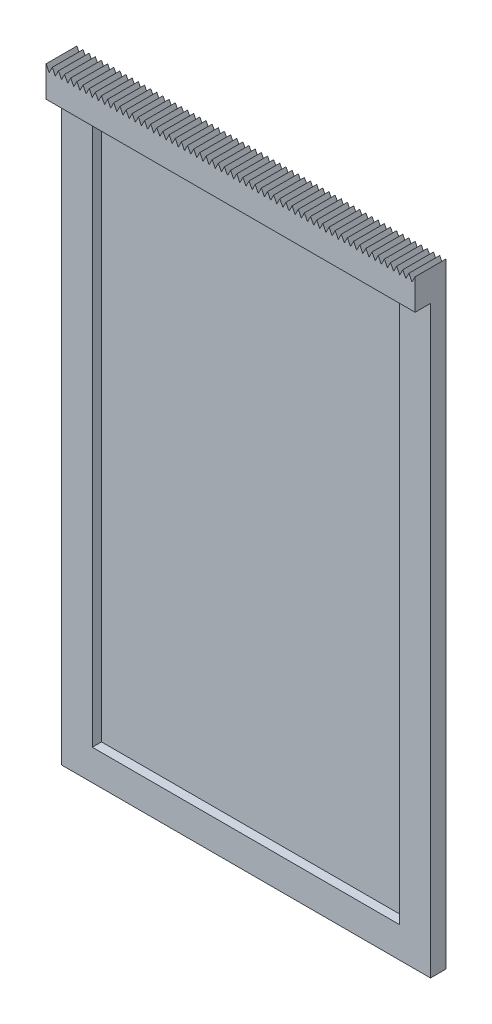
SolidWorks part; units mm, degrees
ref_plane "Alzado" through (0, 0, 0) normal (0, 0, 1) x (1, 0, 0)
ref_plane "Planta" through (0, 0, 0) normal (0, 1, 0) x (1, 0, 0)
ref_plane "Vista lateral" through (0, 0, 0) normal (1, 0, 0) x (0, 0, -1)
sketch "Croquis2" plane through (0, 0, 0) normal (0, 0, 1) x (1, 0, 0)
  line L0 (-60, 100) -> (60, -100) construction
  line L1 (-60, 100) -> (60, 100)
  line L2 (-60, 100) -> (-60, -100)
  line L3 (-60, -100) -> (60, -100)
  line L4 (60, 100) -> (60, -100)
  point P4 (0, 0)
  dimension "D1" = 120
  dimension "D2" = 200
extrude "Saliente-Extruir1" add sketch "Croquis2" along normal blind 5
sketch "Croquis3" plane through (0, 0, 5) normal (0, 0, 1) x (1, 0, 0)
  line L0 (-60, 100) -> (-60, -100) construction
  line L1 (-50, 90) -> (50, 90)
  line L2 (-50, 90) -> (-50, -90)
  line L3 (-50, -90) -> (50, -90)
  line L4 (50, 90) -> (50, -90)
  line L5 (-50, 90) -> (50, -90) construction
  line L6 (60, 100) -> (-60, 100) construction
  point P6 (0, 0)
  dimension "D1" = 10
  dimension "D2" = 10
extrude "Cortar-Extruir1" cut sketch "Croquis3" against normal blind 3
sketch "Croquis4" plane through (0, 0, 5) normal (0, 0, 1) x (1, 0, 0)
  line L0 (60, -100) -> (60, 100) construction
  line L1 (-60, 100) -> (60, 100)
  line L2 (-60, 100) -> (-60, 90)
  line L3 (-60, 90) -> (60, 90)
  line L4 (60, 100) -> (60, 90)
  dimension "D1" = 10
extrude "Saliente-Extruir3" add sketch "Croquis4" along normal blind 5
sketch "Croquis5" plane through (0, 100, 0) normal (0, 1, 0) x (1, 0, 0)
  line L0 (-60, -10) -> (-59, -8)
  line L1 (-59, -8) -> (-58, -10)
  line L2 (60, -10) -> (-60, -10) construction
  line L3 (-60, -10) -> (-58, -10)
  line L4 (-58, -10) -> (-56, -10)
  line L5 (-57, -8) -> (-56, -10)
  line L6 (-58, -10) -> (-57, -8)
  line L7 (-56, -10) -> (-54, -10)
  line L8 (-55, -8) -> (-54, -10)
  line L9 (-56, -10) -> (-55, -8)
  line L10 (-54, -10) -> (-52, -10)
  line L11 (-53, -8) -> (-52, -10)
  line L12 (-54, -10) -> (-53, -8)
  line L13 (-52, -10) -> (-50, -10)
  line L14 (-51, -8) -> (-50, -10)
  line L15 (-52, -10) -> (-51, -8)
  line L16 (-50, -10) -> (-48, -10)
  line L17 (-49, -8) -> (-48, -10)
  line L18 (-50, -10) -> (-49, -8)
  line L19 (-48, -10) -> (-46, -10)
  line L20 (-47, -8) -> (-46, -10)
  line L21 (-48, -10) -> (-47, -8)
  line L22 (-46, -10) -> (-44, -10)
  line L23 (-45, -8) -> (-44, -10)
  line L24 (-46, -10) -> (-45, -8)
  line L25 (-44, -10) -> (-42, -10)
  line L26 (-43, -8) -> (-42, -10)
  line L27 (-44, -10) -> (-43, -8)
  line L28 (-42, -10) -> (-40, -10)
  line L29 (-41, -8) -> (-40, -10)
  line L30 (-42, -10) -> (-41, -8)
  line L31 (-40, -10) -> (-38, -10)
  line L32 (-39, -8) -> (-38, -10)
  line L33 (-40, -10) -> (-39, -8)
  line L34 (-38, -10) -> (-36, -10)
  line L35 (-37, -8) -> (-36, -10)
  line L36 (-38, -10) -> (-37, -8)
  line L37 (-36, -10) -> (-34, -10)
  line L38 (-35, -8) -> (-34, -10)
  line L39 (-36, -10) -> (-35, -8)
  line L40 (-34, -10) -> (-32, -10)
  line L41 (-33, -8) -> (-32, -10)
  line L42 (-34, -10) -> (-33, -8)
  line L43 (-32, -10) -> (-30, -10)
  line L44 (-31, -8) -> (-30, -10)
  line L45 (-32, -10) -> (-31, -8)
  line L46 (-30, -10) -> (-28, -10)
  line L47 (-29, -8) -> (-28, -10)
  line L48 (-30, -10) -> (-29, -8)
  line L49 (-28, -10) -> (-26, -10)
  line L50 (-27, -8) -> (-26, -10)
  line L51 (-28, -10) -> (-27, -8)
  line L52 (-26, -10) -> (-24, -10)
  line L53 (-25, -8) -> (-24, -10)
  line L54 (-26, -10) -> (-25, -8)
  line L55 (-24, -10) -> (-22, -10)
  line L56 (-23, -8) -> (-22, -10)
  line L57 (-24, -10) -> (-23, -8)
  line L58 (-22, -10) -> (-20, -10)
  line L59 (-21, -8) -> (-20, -10)
  line L60 (-22, -10) -> (-21, -8)
  line L61 (-20, -10) -> (-18, -10)
  line L62 (-19, -8) -> (-18, -10)
  line L63 (-20, -10) -> (-19, -8)
  line L64 (-18, -10) -> (-16, -10)
  line L65 (-17, -8) -> (-16, -10)
  line L66 (-18, -10) -> (-17, -8)
  line L67 (-16, -10) -> (-14, -10)
  line L68 (-15, -8) -> (-14, -10)
  line L69 (-16, -10) -> (-15, -8)
  line L70 (-14, -10) -> (-12, -10)
  line L71 (-13, -8) -> (-12, -10)
  line L72 (-14, -10) -> (-13, -8)
  line L73 (-12, -10) -> (-10, -10)
  line L74 (-11, -8) -> (-10, -10)
  line L75 (-12, -10) -> (-11, -8)
  line L76 (-10, -10) -> (-8, -10)
  line L77 (-9, -8) -> (-8, -10)
  line L78 (-10, -10) -> (-9, -8)
  line L79 (-8, -10) -> (-6, -10)
  line L80 (-7, -8) -> (-6, -10)
  line L81 (-8, -10) -> (-7, -8)
  line L82 (-6, -10) -> (-4, -10)
  line L83 (-5, -8) -> (-4, -10)
  line L84 (-6, -10) -> (-5, -8)
  line L85 (-4, -10) -> (-2, -10)
  line L86 (-3, -8) -> (-2, -10)
  line L87 (-4, -10) -> (-3, -8)
  line L88 (-2, -10) -> (0, -10)
  line L89 (-1, -8) -> (0, -10)
  line L90 (-2, -10) -> (-1, -8)
  line L91 (0, -10) -> (2, -10)
  line L92 (1, -8) -> (2, -10)
  line L93 (0, -10) -> (1, -8)
  line L94 (2, -10) -> (4, -10)
  line L95 (3, -8) -> (4, -10)
  line L96 (2, -10) -> (3, -8)
  line L97 (4, -10) -> (6, -10)
  line L98 (5, -8) -> (6, -10)
  line L99 (4, -10) -> (5, -8)
  line L100 (6, -10) -> (8, -10)
  line L101 (7, -8) -> (8, -10)
  line L102 (6, -10) -> (7, -8)
  line L103 (8, -10) -> (10, -10)
  line L104 (9, -8) -> (10, -10)
  line L105 (8, -10) -> (9, -8)
  line L106 (10, -10) -> (12, -10)
  line L107 (11, -8) -> (12, -10)
  line L108 (10, -10) -> (11, -8)
  line L109 (12, -10) -> (14, -10)
  line L110 (13, -8) -> (14, -10)
  line L111 (12, -10) -> (13, -8)
  line L112 (14, -10) -> (16, -10)
  line L113 (15, -8) -> (16, -10)
  line L114 (14, -10) -> (15, -8)
  line L115 (16, -10) -> (18, -10)
  line L116 (17, -8) -> (18, -10)
  line L117 (16, -10) -> (17, -8)
  line L118 (18, -10) -> (20, -10)
  line L119 (19, -8) -> (20, -10)
  line L120 (18, -10) -> (19, -8)
  line L121 (20, -10) -> (22, -10)
  line L122 (21, -8) -> (22, -10)
  line L123 (20, -10) -> (21, -8)
  line L124 (22, -10) -> (24, -10)
  line L125 (23, -8) -> (24, -10)
  line L126 (22, -10) -> (23, -8)
  line L127 (24, -10) -> (26, -10)
  line L128 (25, -8) -> (26, -10)
  line L129 (24, -10) -> (25, -8)
  line L130 (26, -10) -> (28, -10)
  line L131 (27, -8) -> (28, -10)
  line L132 (26, -10) -> (27, -8)
  line L133 (28, -10) -> (30, -10)
  line L134 (29, -8) -> (30, -10)
  line L135 (28, -10) -> (29, -8)
  line L136 (30, -10) -> (32, -10)
  line L137 (31, -8) -> (32, -10)
  line L138 (30, -10) -> (31, -8)
  line L139 (32, -10) -> (34, -10)
  line L140 (33, -8) -> (34, -10)
  line L141 (32, -10) -> (33, -8)
  line L142 (34, -10) -> (36, -10)
  line L143 (35, -8) -> (36, -10)
  line L144 (34, -10) -> (35, -8)
  line L145 (36, -10) -> (38, -10)
  line L146 (37, -8) -> (38, -10)
  line L147 (36, -10) -> (37, -8)
  line L148 (38, -10) -> (40, -10)
  line L149 (39, -8) -> (40, -10)
  line L150 (38, -10) -> (39, -8)
  line L151 (40, -10) -> (42, -10)
  line L152 (41, -8) -> (42, -10)
  line L153 (40, -10) -> (41, -8)
  line L154 (42, -10) -> (44, -10)
  line L155 (43, -8) -> (44, -10)
  line L156 (42, -10) -> (43, -8)
  line L157 (44, -10) -> (46, -10)
  line L158 (45, -8) -> (46, -10)
  line L159 (44, -10) -> (45, -8)
  line L160 (46, -10) -> (48, -10)
  line L161 (47, -8) -> (48, -10)
  line L162 (46, -10) -> (47, -8)
  line L163 (48, -10) -> (50, -10)
  line L164 (49, -8) -> (50, -10)
  line L165 (48, -10) -> (49, -8)
  line L166 (50, -10) -> (52, -10)
  line L167 (51, -8) -> (52, -10)
  line L168 (50, -10) -> (51, -8)
  line L169 (52, -10) -> (54, -10)
  line L170 (53, -8) -> (54, -10)
  line L171 (52, -10) -> (53, -8)
  line L172 (54, -10) -> (56, -10)
  line L173 (55, -8) -> (56, -10)
  line L174 (54, -10) -> (55, -8)
  line L175 (56, -10) -> (58, -10)
  line L176 (57, -8) -> (58, -10)
  line L177 (56, -10) -> (57, -8)
  line L178 (58, -10) -> (60, -10)
  line L179 (59, -8) -> (60, -10)
  line L180 (58, -10) -> (59, -8)
  point P3 (-59, -10)
  dimension "D1" = 2
  dimension "D2" = 2
  dimension "D3" = 60
extrude "Cortar-Extruir2" cut sketch "Croquis5" against normal blind 10 contours L4 L5 L6 | L3 L1 L0 | L7 L8 L9 | L13 L14 L15 | L10 L11 L12 | L16 L17 L18 | L19 L20 L21 | L22 L23 L24 | L28 L29 L30 | L25 L26 L27 | L58 L59 L60 | L55 L56 L57 | L52 L53 L54 | L49 L50 L51 | L46 L47 L48 | L43 L44 L45 | L40 L41 L42 | L37 L38 L39 | L34 L35 L36 | L31 L32 L33 | L61 L62 L63 | L64 L65 L66 | L67 L68 L69 | L70 L71 L72 | L73 L74 L75 | L76 L77 L78 | L79 L80 L81 | L82 L83 L84 | L85 L86 L87 | L88 L89 L90 | L178 L179 L180 | L175 L176 L177 | L172 L173 L174 | L169 L170 L171 | L166 L167 L168 | L163 L164 L165 | L160 L161 L162 | L157 L158 L159 | L154 L155 L156 | L151 L152 L153 | L148 L149 L150 | L145 L146 L147 | L142 L143 L144 | L124 L125 L126 | L127 L128 L129 | L130 L131 L132 | L133 L134 L135 | L136 L137 L138 | L139 L140 L141 | L106 L107 L108 | L109 L110 L111 | L112 L113 L114 | L115 L116 L117 | L118 L119 L120 | L121 L122 L123 | L100 L101 L102 | L103 L104 L105 | L97 L98 L99 | L94 L95 L96 | L91 L92 L93
sketch "Croquis6" plane through (-60, 0, 0) normal (-1, 0, 0) x (0, 0, 1)
  line L0 (10, 100) -> (0, 100) construction
  line L1 (10, 90) -> (5, 90)
  line L2 (10, 90) -> (10, 100)
  line L3 (10, 100) -> (5, 100)
  line L4 (5, 90) -> (5, 100)
extrude "Saliente-Extruir4" add sketch "Croquis6" against normal blind 120
sketch "Croquis7" plane through (0, 0, 10) normal (0, 0, 1) x (1, 0, 0)
  line L0 (-60, 100) -> (-59, 98)
  line L1 (-59, 98) -> (-58, 100)
  line L2 (60, 100) -> (-60, 100) construction
  line L3 (-58, 100) -> (-60, 100)
  line L4 (-56, 100) -> (-58, 100)
  line L5 (-58, 100) -> (-57, 98)
  line L6 (-57, 98) -> (-56, 100)
  line L7 (-54, 100) -> (-56, 100)
  line L8 (-56, 100) -> (-55, 98)
  line L9 (-55, 98) -> (-54, 100)
  line L10 (-52, 100) -> (-54, 100)
  line L11 (-54, 100) -> (-53, 98)
  line L12 (-53, 98) -> (-52, 100)
  line L13 (-50, 100) -> (-52, 100)
  line L14 (-52, 100) -> (-51, 98)
  line L15 (-51, 98) -> (-50, 100)
  line L16 (-48, 100) -> (-50, 100)
  line L17 (-50, 100) -> (-49, 98)
  line L18 (-49, 98) -> (-48, 100)
  line L19 (-46, 100) -> (-48, 100)
  line L20 (-48, 100) -> (-47, 98)
  line L21 (-47, 98) -> (-46, 100)
  line L22 (-44, 100) -> (-46, 100)
  line L23 (-46, 100) -> (-45, 98)
  line L24 (-45, 98) -> (-44, 100)
  line L25 (-42, 100) -> (-44, 100)
  line L26 (-44, 100) -> (-43, 98)
  line L27 (-43, 98) -> (-42, 100)
  line L28 (-40, 100) -> (-42, 100)
  line L29 (-42, 100) -> (-41, 98)
  line L30 (-41, 98) -> (-40, 100)
  line L31 (-38, 100) -> (-40, 100)
  line L32 (-40, 100) -> (-39, 98)
  line L33 (-39, 98) -> (-38, 100)
  line L34 (-36, 100) -> (-38, 100)
  line L35 (-38, 100) -> (-37, 98)
  line L36 (-37, 98) -> (-36, 100)
  line L37 (-34, 100) -> (-36, 100)
  line L38 (-36, 100) -> (-35, 98)
  line L39 (-35, 98) -> (-34, 100)
  line L40 (-32, 100) -> (-34, 100)
  line L41 (-34, 100) -> (-33, 98)
  line L42 (-33, 98) -> (-32, 100)
  line L43 (-30, 100) -> (-32, 100)
  line L44 (-32, 100) -> (-31, 98)
  line L45 (-31, 98) -> (-30, 100)
  line L46 (-28, 100) -> (-30, 100)
  line L47 (-30, 100) -> (-29, 98)
  line L48 (-29, 98) -> (-28, 100)
  line L49 (-26, 100) -> (-28, 100)
  line L50 (-28, 100) -> (-27, 98)
  line L51 (-27, 98) -> (-26, 100)
  line L52 (-24, 100) -> (-26, 100)
  line L53 (-26, 100) -> (-25, 98)
  line L54 (-25, 98) -> (-24, 100)
  line L55 (-22, 100) -> (-24, 100)
  line L56 (-24, 100) -> (-23, 98)
  line L57 (-23, 98) -> (-22, 100)
  line L58 (-20, 100) -> (-22, 100)
  line L59 (-22, 100) -> (-21, 98)
  line L60 (-21, 98) -> (-20, 100)
  line L61 (-18, 100) -> (-20, 100)
  line L62 (-20, 100) -> (-19, 98)
  line L63 (-19, 98) -> (-18, 100)
  line L64 (-16, 100) -> (-18, 100)
  line L65 (-18, 100) -> (-17, 98)
  line L66 (-17, 98) -> (-16, 100)
  line L67 (-14, 100) -> (-16, 100)
  line L68 (-16, 100) -> (-15, 98)
  line L69 (-15, 98) -> (-14, 100)
  line L70 (-12, 100) -> (-14, 100)
  line L71 (-14, 100) -> (-13, 98)
  line L72 (-13, 98) -> (-12, 100)
  line L73 (-10, 100) -> (-12, 100)
  line L74 (-12, 100) -> (-11, 98)
  line L75 (-11, 98) -> (-10, 100)
  line L76 (-8, 100) -> (-10, 100)
  line L77 (-10, 100) -> (-9, 98)
  line L78 (-9, 98) -> (-8, 100)
  line L79 (-6, 100) -> (-8, 100)
  line L80 (-8, 100) -> (-7, 98)
  line L81 (-7, 98) -> (-6, 100)
  line L82 (-4, 100) -> (-6, 100)
  line L83 (-6, 100) -> (-5, 98)
  line L84 (-5, 98) -> (-4, 100)
  line L85 (-2, 100) -> (-4, 100)
  line L86 (-4, 100) -> (-3, 98)
  line L87 (-3, 98) -> (-2, 100)
  line L88 (0, 100) -> (-2, 100)
  line L89 (-2, 100) -> (-1, 98)
  line L90 (-1, 98) -> (0, 100)
  line L91 (2, 100) -> (0, 100)
  line L92 (0, 100) -> (1, 98)
  line L93 (1, 98) -> (2, 100)
  line L94 (4, 100) -> (2, 100)
  line L95 (2, 100) -> (3, 98)
  line L96 (3, 98) -> (4, 100)
  line L97 (6, 100) -> (4, 100)
  line L98 (4, 100) -> (5, 98)
  line L99 (5, 98) -> (6, 100)
  line L100 (8, 100) -> (6, 100)
  line L101 (6, 100) -> (7, 98)
  line L102 (7, 98) -> (8, 100)
  line L103 (10, 100) -> (8, 100)
  line L104 (8, 100) -> (9, 98)
  line L105 (9, 98) -> (10, 100)
  line L106 (12, 100) -> (10, 100)
  line L107 (10, 100) -> (11, 98)
  line L108 (11, 98) -> (12, 100)
  line L109 (14, 100) -> (12, 100)
  line L110 (12, 100) -> (13, 98)
  line L111 (13, 98) -> (14, 100)
  line L112 (16, 100) -> (14, 100)
  line L113 (14, 100) -> (15, 98)
  line L114 (15, 98) -> (16, 100)
  line L115 (18, 100) -> (16, 100)
  line L116 (16, 100) -> (17, 98)
  line L117 (17, 98) -> (18, 100)
  line L118 (20, 100) -> (18, 100)
  line L119 (18, 100) -> (19, 98)
  line L120 (19, 98) -> (20, 100)
  line L121 (22, 100) -> (20, 100)
  line L122 (20, 100) -> (21, 98)
  line L123 (21, 98) -> (22, 100)
  line L124 (24, 100) -> (22, 100)
  line L125 (22, 100) -> (23, 98)
  line L126 (23, 98) -> (24, 100)
  line L127 (26, 100) -> (24, 100)
  line L128 (24, 100) -> (25, 98)
  line L129 (25, 98) -> (26, 100)
  line L130 (28, 100) -> (26, 100)
  line L131 (26, 100) -> (27, 98)
  line L132 (27, 98) -> (28, 100)
  line L133 (30, 100) -> (28, 100)
  line L134 (28, 100) -> (29, 98)
  line L135 (29, 98) -> (30, 100)
  line L136 (32, 100) -> (30, 100)
  line L137 (30, 100) -> (31, 98)
  line L138 (31, 98) -> (32, 100)
  line L139 (34, 100) -> (32, 100)
  line L140 (32, 100) -> (33, 98)
  line L141 (33, 98) -> (34, 100)
  line L142 (36, 100) -> (34, 100)
  line L143 (34, 100) -> (35, 98)
  line L144 (35, 98) -> (36, 100)
  line L145 (38, 100) -> (36, 100)
  line L146 (36, 100) -> (37, 98)
  line L147 (37, 98) -> (38, 100)
  line L148 (40, 100) -> (38, 100)
  line L149 (38, 100) -> (39, 98)
  line L150 (39, 98) -> (40, 100)
  line L151 (42, 100) -> (40, 100)
  line L152 (40, 100) -> (41, 98)
  line L153 (41, 98) -> (42, 100)
  line L154 (44, 100) -> (42, 100)
  line L155 (42, 100) -> (43, 98)
  line L156 (43, 98) -> (44, 100)
  line L157 (46, 100) -> (44, 100)
  line L158 (44, 100) -> (45, 98)
  line L159 (45, 98) -> (46, 100)
  line L160 (48, 100) -> (46, 100)
  line L161 (46, 100) -> (47, 98)
  line L162 (47, 98) -> (48, 100)
  line L163 (50, 100) -> (48, 100)
  line L164 (48, 100) -> (49, 98)
  line L165 (49, 98) -> (50, 100)
  line L166 (52, 100) -> (50, 100)
  line L167 (50, 100) -> (51, 98)
  line L168 (51, 98) -> (52, 100)
  line L169 (54, 100) -> (52, 100)
  line L170 (52, 100) -> (53, 98)
  line L171 (53, 98) -> (54, 100)
  line L172 (56, 100) -> (54, 100)
  line L173 (54, 100) -> (55, 98)
  line L174 (55, 98) -> (56, 100)
  line L175 (58, 100) -> (56, 100)
  line L176 (56, 100) -> (57, 98)
  line L177 (57, 98) -> (58, 100)
  line L178 (60, 100) -> (58, 100)
  line L179 (58, 100) -> (59, 98)
  line L180 (59, 98) -> (60, 100)
  point P7 (-59, 100)
  dimension "D1" = 2
  dimension "D2" = 2
  dimension "D3" = 60
extrude "Cortar-Extruir3" cut sketch "Croquis7" along direction (0, 0, 1) on the side against the normal blind 10 contours L3 L0 L1 | L4 L5 L6 | L7 L8 L9 | L10 L11 L12 | L13 L14 L15 | L16 L17 L18 | L19 L20 L21 | L22 L23 L24 | L25 L26 L27 | L28 L29 L30 | L31 L32 L33 | L34 L35 L36 | L37 L38 L39 | L40 L41 L42 | L43 L44 L45 | L58 L59 L60 | L55 L56 L57 | L52 L53 L54 | L49 L50 L51 | L46 L47 L48 | L61 L62 L63 | L64 L65 L66 | L67 L68 L69 | L70 L71 L72 | L76 L77 L78 | L73 L74 L75 | L91 L92 L93 | L88 L89 L90 | L85 L86 L87 | L82 L83 L84 | L79 L80 L81 | L103 L104 L105 | L100 L101 L102 | L97 L98 L99 | L94 L95 L96 | L106 L107 L108 | L109 L110 L111 | L112 L113 L114 | L151 L152 L153 | L148 L149 L150 | L145 L146 L147 | L142 L143 L144 | L139 L140 L141 | L136 L137 L138 | L115 L116 L117 | L118 L119 L120 | L121 L122 L123 | L124 L125 L126 | L127 L128 L129 | L130 L131 L132 | L133 L134 L135 | L178 L179 L180 | L175 L176 L177 | L172 L173 L174 | L169 L170 L171 | L166 L167 L168 | L163 L164 L165 | L157 L158 L159 | L160 L161 L162 | L154 L155 L156
